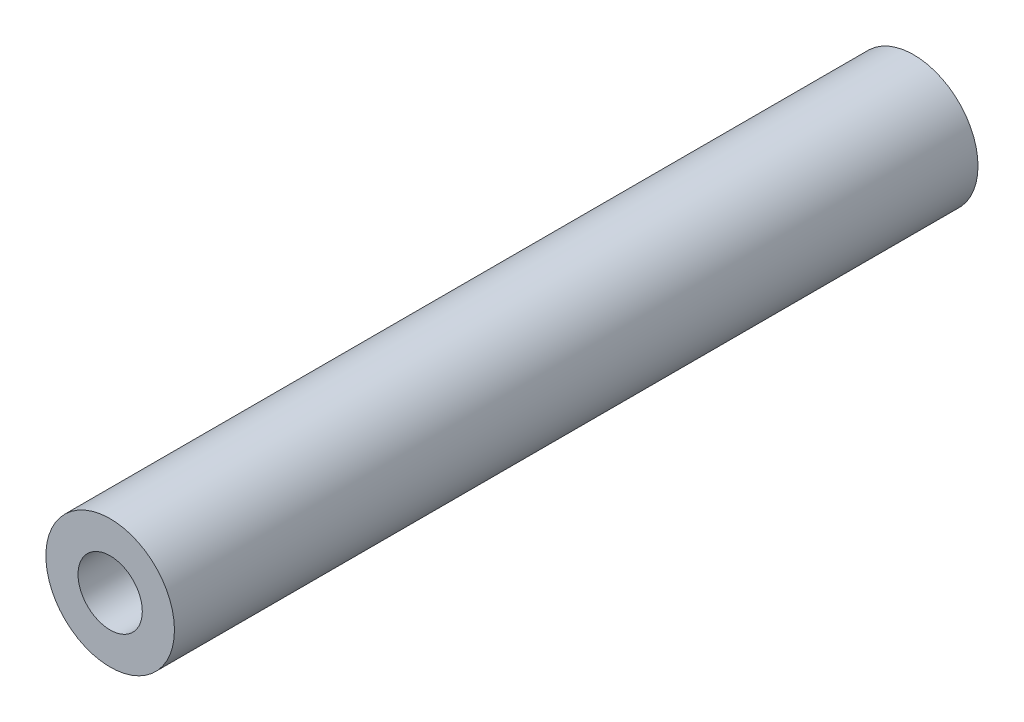
SolidWorks part; units mm, degrees
ref_plane "前视基准面" through (0, 0, 0) normal (0, 0, 1) x (1, 0, 0)
ref_plane "上视基准面" through (0, 0, 0) normal (0, 1, 0) x (1, 0, 0)
ref_plane "右视基准面" through (0, 0, 0) normal (1, 0, 0) x (0, 0, -1)
sketch "草图1" plane through (0, 0, 0) normal (0, 0, 1) x (1, 0, 0)
  circle A0 centre (0, 0) radius 4
  circle A1 centre (0, 0) radius 2
  dimension "D1" = 4
  dimension "D2" = 8
extrude "凸台-拉伸1" add sketch "草图1" along normal mid plane 50
